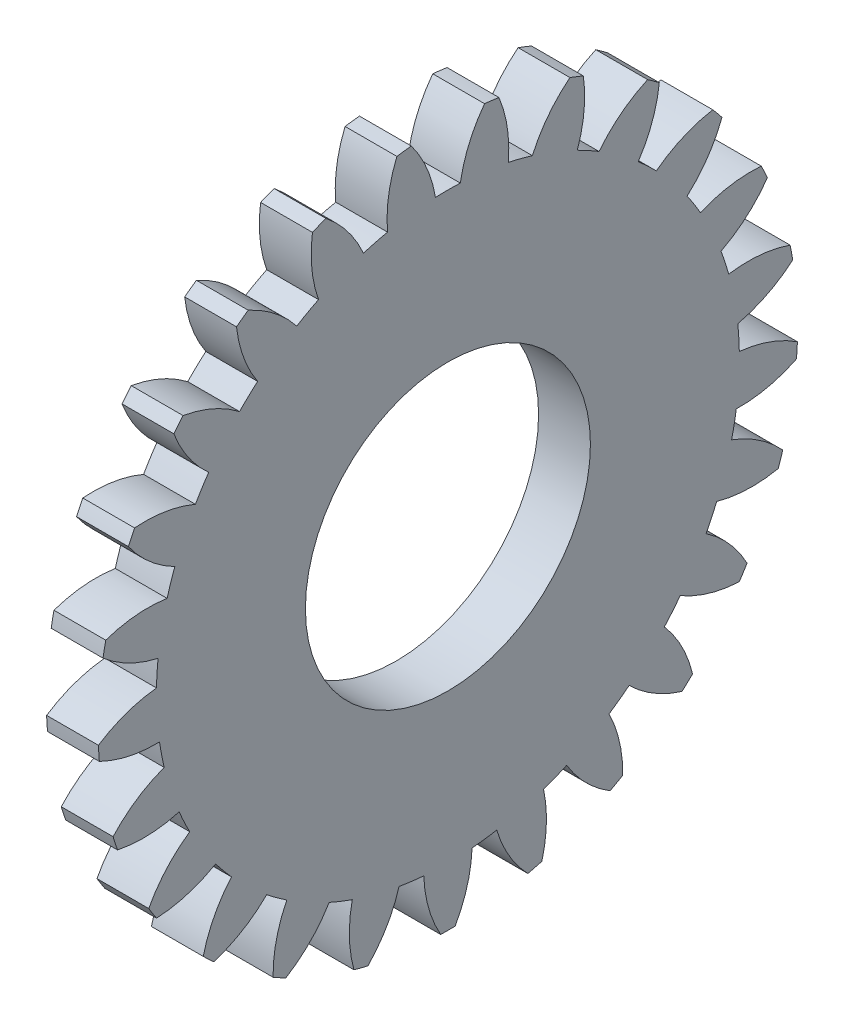
SolidWorks part; units mm, degrees
material "Alliage de zinc AC41A, brut"
ref_plane "Plane1" through (0, 0, 0) normal (0, 0, 1) x (1, 0, 0)
ref_plane "Plane2" through (0, 0, 0) normal (0, 1, 0) x (1, 0, 0)
ref_plane "Plane3" through (0, 0, 0) normal (1, 0, 0) x (0, 0, -1)
sketch "HoldingSke" plane through (0, 0, 0) normal (0, 1, 0) x (1, 0, 0)
  line L0 (0, 0) -> (0.9063, -0.4226)
  line L1 (-15, 0) -> (100, 0) construction
  line L2 (0, 0) -> (-2.1039, 2.3779)
  line L3 (0, 0) -> (-11.863, 4.5341)
  line L4 (0, 0) -> (7.8269, 3.6497)
  line L5 (0, 0) -> (-46.8476, -17.4728)
  line L6 (0, 0) -> (-1.6579, -1.1186)
  line L7 (-2.1039, 2.3779) -> (8.6586, 51.2059)
  line L8 (-76.2, 54.61) -> (-75.9, 54.61)
  line L9 (-71.009, 38.7566) -> (-53.1078, 45.2721)
  line L10 (-76.2, 71.12) -> (104.1128, 71.12)
  line L11 (0, 0) -> (-2, 0)
  line L12 (-76.2, 101.6) -> (-76.162, 101.6)
  line L13 (24.9733, 27.94) -> (52.9518, 28.4284)
  line L14 (24.9733, 27.94) -> (24.9743, 27.94)
  line L15 (24.9733, 27.94) -> (100.4006, 29.5858)
  line L16 (-63.627, -1) -> (-12.827, -1)
  circle A0 centre (0, 0) radius 1
  circle A1 centre (0, 0) radius 11.249
  circle A2 centre (0, 0) radius 37.5
  circle A3 centre (0, 0) radius 5.5
  dimension "MHD" = 22.498
  dimension "Hub_dia" = 75
  dimension "Bore" = 2
  dimension "MBD" = 11
  dimension "Num_teeth" = 25
  dimension "Pitch" = 1
  dimension "Overall_len" = 50
  dimension "Show_teeth" = 25
  dimension "Thickness" = 2
  dimension "OAL" = 50.0001
  dimension "T_dim" = 0.3
  dimension "Ap" = 20
  dimension "H" = 19.05
  dimension "Pitch_radius" = 180.3128
  dimension "Width" = 2
  dimension "Backlash" = 0.038
  dimension "Addendum_fac" = 1
  dimension "Dedendum_fac" = 1.25
  dimension "Clearance_fac" = 0.25
  dimension "Dedendum_add" = 0.001
  dimension "Module" = 1
sketch "BasProSke" plane through (0, 0, 0) normal (0, 1, 0) x (1, 0, 0)
  line L0 (-10, 0) -> (60, 0) construction
  line L1 (0, 0) -> (0, 13.5)
  line L2 (0, 0) -> (2, 0)
  line L3 (2, 0) -> (2, 13.5)
  line L4 (2, 13.5) -> (0, 13.5)
  dimension "Thickness" = 2
  dimension "Diameter" = 27
revolve "Base-Revolve" add sketch "BasProSke" angle 360 about L0
sketch "TooCutSke" plane through (0, 0, 0) normal (1, 0, 0) x (0, 0, -1)
  line L1 (0, 0) -> (0, 107) construction
  line L2 (0, 0) -> (-0.8514, 12.471) construction
  line L3 (0, 0) -> (-3.1282, 24.7619) construction
  line L4 (-0.8514, 12.471) -> (-1.5641, 12.3809) construction
  arc A0 (0.4801, 11.2388) -> (-0.4801, 11.2388) centre (0, 0) ccw
  arc A1 (1.4322, 13.4494) -> (-1.4322, 13.4494) centre (0, 0) ccw
  circle A2 centre (0, 0) radius 12.5 construction
  circle A3 centre (0, 0) radius 11.7462 construction
  arc A4 (-0.4801, 11.2388) -> (-1.4322, 13.4494) centre (-5.4133, 10.4244) ccw
  arc A5 (1.4322, 13.4494) -> (0.4801, 11.2388) centre (5.4133, 10.4244) ccw
  dimension "Root_dia" = 22.498
  dimension "Overcut_dia" = 27.0508
  dimension "Pitch_dia" = 25
  dimension "Base_dia" = 23.4923
  dimension "Flank_rad" = 5
  dimension "Half_ang" = 7.2
  dimension "Half_CT" = 0.7184
extrude "ToothCut" cut sketch "TooCutSke" along normal through all
fillet "Breaks" [suppressed] radius 0.02
fillet "RootFillets" [suppressed] radius 0.251
pattern_circular "TeethCuts" count 25 every 14.4 about axis through (-10, 0, 0) along (1, 0, 0) of "ToothCut", "RootFillets", "Breaks"
sketch "HubNeaOneSke" plane through (0, 0, 0) normal (-1, 0, 0) x (0, 0, 1)
  circle A0 centre (0, 0) radius 11.249
  dimension "Diameter" = 22.498
extrude "HubNearOne" [suppressed] add sketch "HubNeaOneSke" along normal blind 48.0001
sketch "HubNeaBotSke" plane through (0, 0, 0) normal (-1, 0, 0) x (0, 0, 1)
  circle A0 centre (0, 0) radius 11.249
  dimension "Diameter" = 22.498
extrude "HubNearBoth" [suppressed] add sketch "HubNeaBotSke" along normal blind 24
ref_plane "FarPln" through (2, 0, 0) normal (1, 0, 0) x (0, 0, -1)
sketch "HubFarSke" plane through (2, 0, 0) normal (1, 0, 0) x (0, 0, -1)
  circle A0 centre (0, 0) radius 11.249
  dimension "Diameter" = 22.498
extrude "HubFar" [suppressed] add sketch "HubFarSke" along normal blind 24
sketch "BorSke" plane through (0, 0, 0) normal (1, 0, 0) x (0, 0, -1)
  circle A0 centre (0, 0) radius 5.5
  dimension "Diameter" = 11
extrude "Bore" cut sketch "BorSke" along normal mid plane 100.0001
sketch "KeySke" plane through (0, 0, 0) normal (1, 0, 0) x (0, 0, -1)
  line L0 (-0.4, 0) -> (-0.4, 5.8)
  line L1 (-0.4, 5.8) -> (0.4, 5.8)
  line L2 (0.4, 5.8) -> (0.4, 0)
  line L3 (0, 0) -> (0, 34) construction
  line L4 (-0.4, 0) -> (0.4, 0)
  dimension "Offset" = 5.8
  dimension "Width" = 0.8
extrude "Keyway" [suppressed] cut sketch "KeySke" along normal mid plane 100.0001
pattern_circular "Keyway2" [suppressed] count 2 every 90 about axis through (-10, 0, 0) along (1, 0, 0)
equation "' \"Module@HoldingSke\" = 6.35"
equation "' \"Num_teeth@HoldingSke\" = 12"
equation "' \"Ap@HoldingSke\" =  20"
equation "' \"Ap@HoldingSke\" = 20"
equation "' \"Width@HoldingSke\" = 0.5 * 25.4"
equation "' \"Hub_dia@HoldingSke\"= 1 * 25.4"
equation "' \"Hub_dia@HoldingSke\" = 1 * 25.4"
equation "' \"Overall_len@HoldingSke\" = 1.0 * 25.4"
equation "' \"Bore@HoldingSke\" = 0.75 * 25.4"
equation "' \"T_dim@HoldingSke\" = 0.1 * 25.4"
equation "' \"Width@KeySke\" = 0.25 * 25.4"
equation "' \"Show_teeth@HoldingSke\" = 13"
equation "' \"Backlash@HoldingSke\" = 0.009 * 25.4"
equation "' \"Addendum_fac@HoldingSke\" = 1.0"
equation "' \"Dedendum_fac@HoldingSke\" = 1.25"
equation "' \"Dedendum_add@HoldingSke\" = 0.00005 * 25.4"
equation "' \"Clearance_fac@HoldingSke\" = 0.25"
equation "\"Pitch@HoldingSke\" = 1 / \"Module@HoldingSke\""
equation "\"Overcut_dia@TooCutSke\" = (\"Num_teeth@HoldingSke\" + 2 * \"Addendum_fac@HoldingSke\") / \"Pitch@HoldingSke\" + 0.002 * 25.4"
equation "\"Pitch_dia@TooCutSke\" = \"Num_teeth@HoldingSke\" / \"Pitch@HoldingSke\""
equation "\"Base_dia@TooCutSke\" = \"Num_teeth@HoldingSke\" / \"Pitch@HoldingSke\" * cos((\"Ap@HoldingSke\"  * 3.14159265 / 180))"
equation "\"Root_dia@TooCutSke\" = (\"Num_teeth@HoldingSke\" + 2) / \"Pitch@HoldingSke\" - 2 * (\"Addendum_fac@HoldingSke\" + \"Dedendum_fac@HoldingSke\") / \"Pitch@HoldingSke\" - \"Dedendum_add@HoldingSke\" * 2"
equation "\"Half_ang@TooCutSke\" = 180 / \"Num_teeth@HoldingSke\""
equation "\"Half_CT@TooCutSke\" = \"Num_teeth@HoldingSke\" / \"Pitch@HoldingSke\" * sin((3.14159265 / 2 / \"Num_teeth@HoldingSke\")) / 2 - 7 * \"Backlash@HoldingSke\" / 4"
equation "\"Flank_rad@TooCutSke\" = \"Num_teeth@HoldingSke\" / \"Pitch@HoldingSke\" / 5"
equation "\"Radius@RootFillets\" = \"Clearance_fac@HoldingSke\" / \"Pitch@HoldingSke\" + \"Dedendum_add@HoldingSke\""
equation "\"Break_rad@Breaks\" = 0.02 / \"Pitch@HoldingSke\""
equation "\"Thickness@HoldingSke\" = \"Width@HoldingSke\""
equation "\"OAL@HoldingSke\" = \"Thickness@HoldingSke\""
equation "\"MHD@HoldingSke\" = (\"Num_teeth@HoldingSke\" + 2) / \"Pitch@HoldingSke\" - 2 * (\"Addendum_fac@HoldingSke\" + \"Dedendum_fac@HoldingSke\")  / \"Pitch@HoldingSke\" - \"Dedendum_add@HoldingSke\" * 2"
equation "\"MHD@HoldingSke\" = ((sgn( \"MHD@HoldingSke\" - \"Hub_dia@HoldingSke\" )-1)*( \"MHD@HoldingSke\" - \"Hub_dia@HoldingSke\" ))/-2+ \"Hub_dia@HoldingSke\""
equation "\"OAL@HoldingSke\" = ((sgn( \"OAL@HoldingSke\" - \"Overall_len@HoldingSke\" )+1)*( \"OAL@HoldingSke\" - \"Overall_len@HoldingSke\" ))/2 + \"Overall_len@HoldingSke\" + 0.000002 * 25.4"
equation "\"Num_teeth@TeethCuts\" = int( \"Show_teeth@HoldingSke\" ) + 1"
equation "\"Num_teeth@TeethCuts\" = ((sgn( \"Num_teeth@TeethCuts\" - \"Num_teeth@HoldingSke\" )-1)*( \"Num_teeth@TeethCuts\" - \"Num_teeth@HoldingSke\" ))/-2+ \"Num_teeth@HoldingSke\""
equation "\"Num_teeth@TeethCuts\" = ((sgn( \"Num_teeth@TeethCuts\" - 2.0)+1)*( \"Num_teeth@TeethCuts\" - 2.0))/2 +2.0"
equation "\"Angle@TeethCuts\" = 360.0 / \"Num_teeth@HoldingSke\""
equation "\"Diameter@BasProSke\" = (\"Num_teeth@HoldingSke\" + 2 * \"Addendum_fac@HoldingSke\") / \"Pitch@HoldingSke\""
equation "\"Thickness@BasProSke\"  = \"Thickness@HoldingSke\""
equation "' \"Fillet_rad@BasProSke\" =  \"Thickness@HoldingSke\" * 0.05"
equation "' \"Fillet_rad@BasProSke\" = \"Thickness@HoldingSke\" * 0.05"
equation "\"MHD@HoldingSke\" = ((sgn( \"MHD@HoldingSke\" - \"Root_dia@TooCutSke\" )-1)*( \"MHD@HoldingSke\" - \"Root_dia@TooCutSke\" ))/-2+ \"Root_dia@TooCutSke\""
equation "\"Diameter@HubNeaOneSke\" = \"MHD@HoldingSke\""
equation "\"Length@HubNearOne\" = \"OAL@HoldingSke\" - \"Thickness@BasProSke\""
equation "\"Diameter@HubNeaBotSke\" = \"MHD@HoldingSke\""
equation "\"Length@HubNearBoth\" = ( \"OAL@HoldingSke\" - \"Thickness@BasProSke\" ) / 2.0"
equation "\"Thickness@FarPln\" = \"Thickness@BasProSke\""
equation "\"Diameter@HubFarSke\" = \"MHD@HoldingSke\""
equation "\"Length@HubFar\" = ( \"OAL@HoldingSke\" - \"Thickness@BasProSke\" ) / 2.0"
equation "\"Diameter@BorSke\" = \"MBD@HoldingSke\""
equation "\"D1@Bore\" = \"OAL@HoldingSke\" * 2.0"
equation "\"D1@Keyway\" = \"OAL@HoldingSke\" * 2.0"
equation "\"Offset@KeySke\" = \"T_dim@HoldingSke\" + \"MBD@HoldingSke\" / 2.0"
